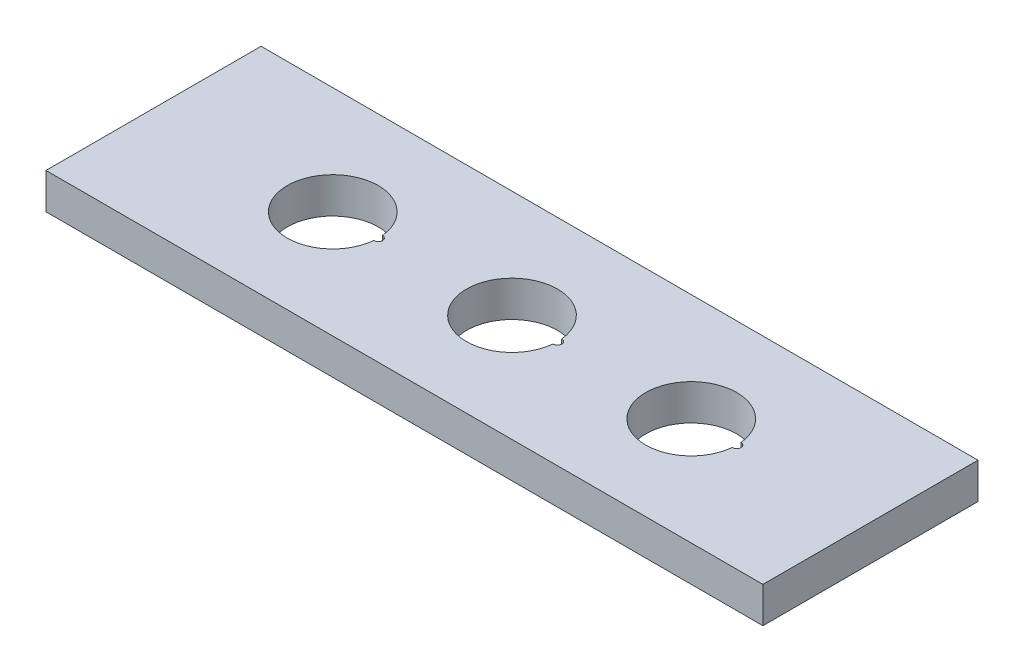
SolidWorks part; units mm, degrees
ref_plane "Front Plane" through (0, 0, 0) normal (0, 0, 1) x (1, 0, 0)
ref_plane "Top Plane" through (0, 0, 0) normal (0, 1, 0) x (1, 0, 0)
ref_plane "Right Plane" through (0, 0, 0) normal (1, 0, 0) x (0, 0, -1)
sketch "Sketch1" plane through (0, 0, 0) normal (0, 1, 0) x (1, 0, 0)
  line L1 (-50, 15) -> (50, 15)
  line L2 (-50, 15) -> (-50, -15)
  line L3 (-50, -15) -> (50, -15)
  line L4 (50, 15) -> (50, -15)
  circle A0 centre (25, 0) radius 6.35 construction
  arc A1 (31.3217, 0.5993) -> (31.3217, -0.5993) centre (31.35, 0) cw
  arc A2 (31.3217, 0.5993) -> (31.3217, -0.5993) centre (25, 0) ccw
  arc A3 (6.3217, 0.5993) -> (6.3217, -0.5993) centre (6.35, 0) cw
  arc A4 (6.3217, 0.5993) -> (6.3217, -0.5993) centre (0, 0) ccw
  arc A5 (-18.6783, 0.5993) -> (-18.6783, -0.5993) centre (-18.65, 0) cw
  arc A6 (-18.6783, 0.5993) -> (-18.6783, -0.5993) centre (-25, 0) ccw
  point P4 (0, 15)
  point P6 (50, 0)
  dimension "D3" = 12.7
  dimension "D4" = 0.6
  dimension "D1" = 100
  dimension "D2" = 30
  dimension "D6" = 25
  dimension "D5" = 3
extrude "Boss-Extrude1" add sketch "Sketch1" along normal blind 5
